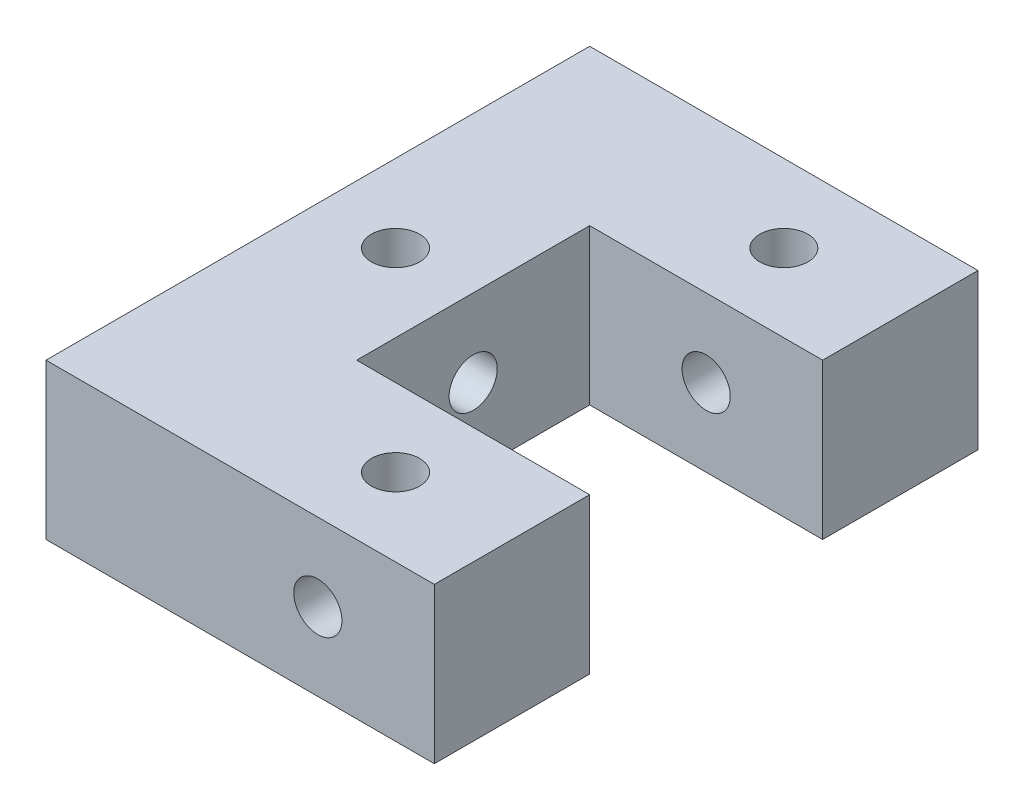
SolidWorks part; units mm, degrees
ref_plane "前视基准面" through (0, 0, 0) normal (0, 0, 1) x (1, 0, 0)
ref_plane "上视基准面" through (0, 0, 0) normal (0, 1, 0) x (1, 0, 0)
ref_plane "右视基准面" through (0, 0, 0) normal (1, 0, 0) x (0, 0, -1)
other "Configuration Table"
sketch "草图1" plane through (0, 0, 0) normal (0, 1, 0) x (1, 0, 0)
  line L0 (0, 0) -> (25, 0)
  line L1 (25, 0) -> (25, -10)
  line L2 (25, -10) -> (10, -10)
  line L3 (10, -10) -> (10, -25)
  line L4 (10, -25) -> (25, -25)
  line L5 (25, -25) -> (25, -35)
  line L6 (25, -35) -> (0, -35)
  line L7 (0, -35) -> (0, 0)
  circle A0 centre (5, -17.5) radius 1.55
  circle A1 centre (17.5, -5) radius 1.55
  circle A2 centre (17.5, -30) radius 1.55
  point P17 (21.5029, -28.7585)
  dimension "D7" = 3.1
  dimension "D1" = 15
  dimension "D2" = 10
  dimension "D3" = 10
  dimension "D4" = 10
  dimension "D5" = 15
  dimension "D6" = 15
  dimension "D8" = 5
  dimension "D9" = 5
  dimension "D10" = 5
  dimension "D11" = 7.5
  dimension "D12" = 7.5
  dimension "D13" = 7.5
extrude "凸台-拉伸1" add sketch "草图1" along normal blind 10
sketch "草图3" plane through (0, 0, 0) normal (-1, 0, 0) x (0, 0, 1)
  line L0 (0, 0) -> (35, 0) construction
  line L1 (35, 10) -> (35, 0) construction
  circle A0 centre (17.5, 5) radius 1.55
  dimension "D1" = 3.1
  dimension "D2" = 5
  dimension "D3" = 17.5
extrude "切除-拉伸1" cut sketch "草图3" against normal up to surface (10 mm away) up to face at (10, 5, 17.5)
sketch "草图4" plane through (0, 0, 35) normal (0, 0, 1) x (1, 0, 0)
  line L0 (0, 0) -> (25, 0) construction
  line L1 (25, 10) -> (25, 0) construction
  circle A0 centre (17.5, 5) radius 1.55
  dimension "D3" = 3.1
  dimension "D1" = 5
  dimension "D2" = 7.5
extrude "切除-拉伸2" cut sketch "草图4" against normal up to surface (35 mm away) up to face at (12.5, 5, 0)
